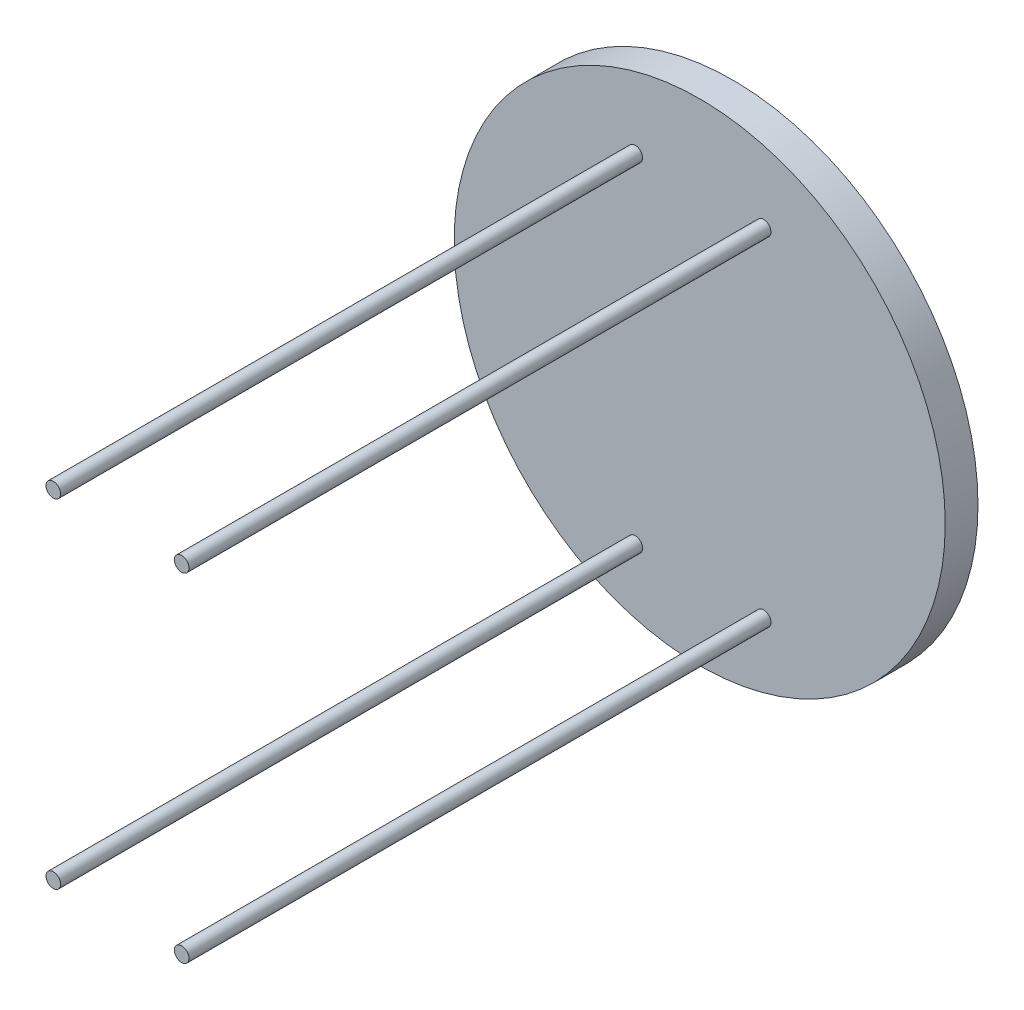
SolidWorks part; units mm, degrees
ref_plane "Front Plane" through (0, 0, 0) normal (0, 0, 1) x (1, 0, 0)
ref_plane "Top Plane" through (0, 0, 0) normal (0, 1, 0) x (1, 0, 0)
ref_plane "Right Plane" through (0, 0, 0) normal (1, 0, 0) x (0, 0, -1)
sketch "Sketch1" plane through (0, 0, 943.5108) normal (0, 0, 1) x (1, 0, 0)
  circle A0 centre (833.9306, -1197.1664) radius 1304.0928
extrude "Boss-Extrude1" add sketch "Sketch1" against normal blind 174
sketch "Sketch3" plane through (0, 0, 943.5108) normal (0, 0, 1) x (1, 0, 0)
  circle A0 centre (1173.6392, -317.2016) radius 38.7717
  circle A1 centre (491.7651, -317.2016) radius 38.7717
  circle A2 centre (491.7651, -2112.8608) radius 38.7717
  circle A3 centre (1173.6392, -2112.8608) radius 38.7717
  dimension "D1" = 77.5434
  dimension "D2" = 77.5434
  dimension "D3" = 77.5434
  dimension "D4" = 77.5434
extrude "Boss-Extrude2" add sketch "Sketch3" along normal blind 3091
